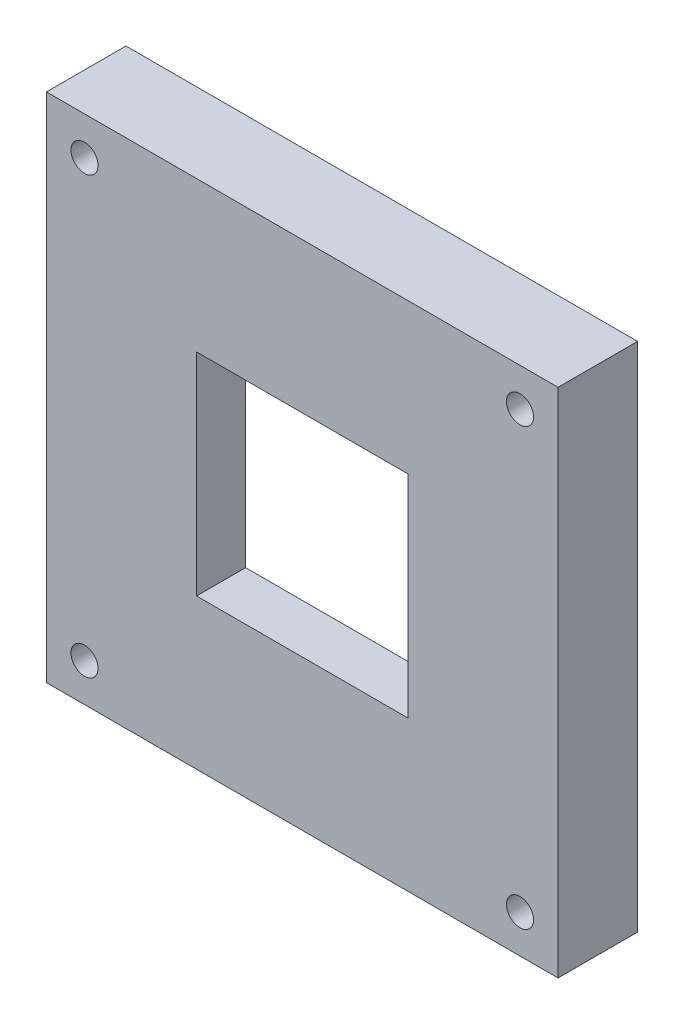
SolidWorks part; units mm, degrees
material "ABS"
ref_plane "Front Plane" through (0, 0, 0) normal (0, 0, 1) x (1, 0, 0)
ref_plane "Top Plane" through (0, 0, 0) normal (0, 1, 0) x (1, 0, 0)
ref_plane "Right Plane" through (0, 0, 0) normal (1, 0, 0) x (0, 0, -1)
sketch "ｽｹｯﾁ1" plane through (0, 0, 0) normal (0, 0, 1) x (1, 0, 0)
  line L0 (19, -19) -> (19, 19) construction
  line L1 (-19.25, -19.25) -> (19.25, -19.25)
  line L2 (-19.25, -19.25) -> (-19.25, 19.25)
  line L3 (-19.25, 19.25) -> (19.25, 19.25)
  line L4 (19.25, -19.25) -> (19.25, 19.25)
  line L5 (-19.25, -19.25) -> (19.25, 19.25) construction
  line L6 (-19.25, 19.25) -> (19.25, -19.25) construction
  line L7 (19, 19) -> (-19, 19) construction
  line L8 (-30.25, 30.25) -> (30.25, 30.25)
  line L9 (30.25, -30.25) -> (30.25, 30.25)
  line L10 (-30.25, -30.25) -> (30.25, -30.25)
  line L11 (-30.25, -30.25) -> (-30.25, 30.25)
  point P0 (0, 0)
  dimension "D1" = 0.25
  dimension "D2" = 0.25
  dimension "D3" = 11
extrude "ﾎﾞｽ - 押し出し1" add sketch "ｽｹｯﾁ1" along normal blind 7 and the other way blind 2.4
ref_plane "平面1" through (0, 0, 1.2) normal (0, 0, 1) x (1, 0, 0)
sketch "ｽｹｯﾁ2" plane through (0, 0, 1.2) normal (0, 0, 1) x (1, 0, 0)
  line L0 (-19.25, 19.25) -> (-19.25, -19.25) construction
  line L1 (-19.25, -19.25) -> (19.25, -19.25) construction
  line L2 (19.25, -19.25) -> (19.25, 19.25) construction
  line L3 (19.25, 19.25) -> (-19.25, 19.25) construction
  line L4 (-19.25, 19.25) -> (-19.25, -19.25)
  line L5 (-19.25, -19.25) -> (19.25, -19.25)
  line L6 (19.25, -19.25) -> (19.25, 19.25)
  line L7 (19.25, 19.25) -> (-19.25, 19.25)
  line L9 (-12.5, -12.5) -> (12.5, -12.5)
  line L10 (-12.5, -12.5) -> (-12.5, 12.5)
  line L11 (-12.5, 12.5) -> (12.5, 12.5)
  line L12 (12.5, -12.5) -> (12.5, 12.5)
  line L13 (-12.5, -12.5) -> (12.5, 12.5) construction
  line L14 (-12.5, 12.5) -> (12.5, -12.5) construction
  point P2 (0, 0)
  dimension "D1" = 25
extrude "ﾎﾞｽ - 押し出し3" add sketch "ｽｹｯﾁ2" along normal up to surface (5.8 mm away) up to face at (0, 0, 7)
sketch "ｽｹｯﾁ3" plane through (0, 0, -2.4) normal (0, 0, -1) x (-1, 0, 0)
  line L0 (-19.25, 20.75) -> (19.25, 20.75)
  line L2 (-19.25, 19.25) -> (19.25, 19.25) construction
  line L3 (-19.25, -19.25) -> (-19.25, 19.25) construction
  line L4 (-19.25, 24.95) -> (19.25, 24.95)
  line L5 (20.75, 19.25) -> (20.75, -19.25)
  line L6 (24.95, 19.25) -> (24.95, -19.25)
  line L7 (19.25, -20.75) -> (-19.25, -20.75)
  line L8 (19.25, -24.95) -> (-19.25, -24.95)
  line L9 (-20.75, -19.25) -> (-20.75, 19.25)
  line L10 (-24.95, -19.25) -> (-24.95, 19.25)
  arc A0 (19.25, 20.75) -> (20.75, 19.25) centre (19.25, 19.25) cw
  arc A1 (19.25, 24.95) -> (24.95, 19.25) centre (19.25, 19.25) cw
  arc A2 (20.75, -19.25) -> (19.25, -20.75) centre (19.25, -19.25) cw
  arc A3 (24.95, -19.25) -> (19.25, -24.95) centre (19.25, -19.25) cw
  arc A4 (-19.25, -20.75) -> (-20.75, -19.25) centre (-19.25, -19.25) cw
  arc A5 (-19.25, -24.95) -> (-24.95, -19.25) centre (-19.25, -19.25) cw
  arc A6 (-20.75, 19.25) -> (-19.25, 20.75) centre (-19.25, 19.25) cw
  arc A7 (-24.95, 19.25) -> (-19.25, 24.95) centre (-19.25, 19.25) cw
  point P40 (0, 0)
  dimension "D1" = 1.5
  dimension "D2" = 4.2
  dimension "D3" = 4
extrude "ｶｯﾄ - 押し出し1" cut sketch "ｽｹｯﾁ3" against normal blind 2.4 contours A7 L10 A5 L8 A3 L6 A1 L4 L9 A6 L0 A0 L5 A2 L7 A4
sketch "ｽｹｯﾁ5" plane through (0, 0, -2.4) normal (0, 0, -1) x (-1, 0, 0)
  line L0 (-30.25, 30.25) -> (30.25, 30.25) construction
  line L1 (-30.25, -30.25) -> (-30.25, 30.25) construction
  circle A0 centre (-25.75, 25.75) radius 1.6
  circle A1 centre (25.75, 25.75) radius 1.6
  circle A2 centre (25.75, -25.75) radius 1.6
  circle A3 centre (-25.75, -25.75) radius 1.6
  point P2 (30.3172, 32.4533)
  point P5 (0, 0)
  point P15 (0, 0)
  dimension "D1" = 3.2
  dimension "D2" = 4.5
  dimension "D3" = 4.5
  dimension "D4" = 4
extrude "ｶｯﾄ - 押し出し2" cut sketch "ｽｹｯﾁ5" against normal through all both and the other way through all
sketch "ｽｹｯﾁ6" plane through (0, 0, 1.2) normal (0, 0, -1) x (-1, 0, 0)
  circle A0 centre (-17, 17) radius 1.15
  point P2 (-17, 17)
  dimension "D1" = 2.3
